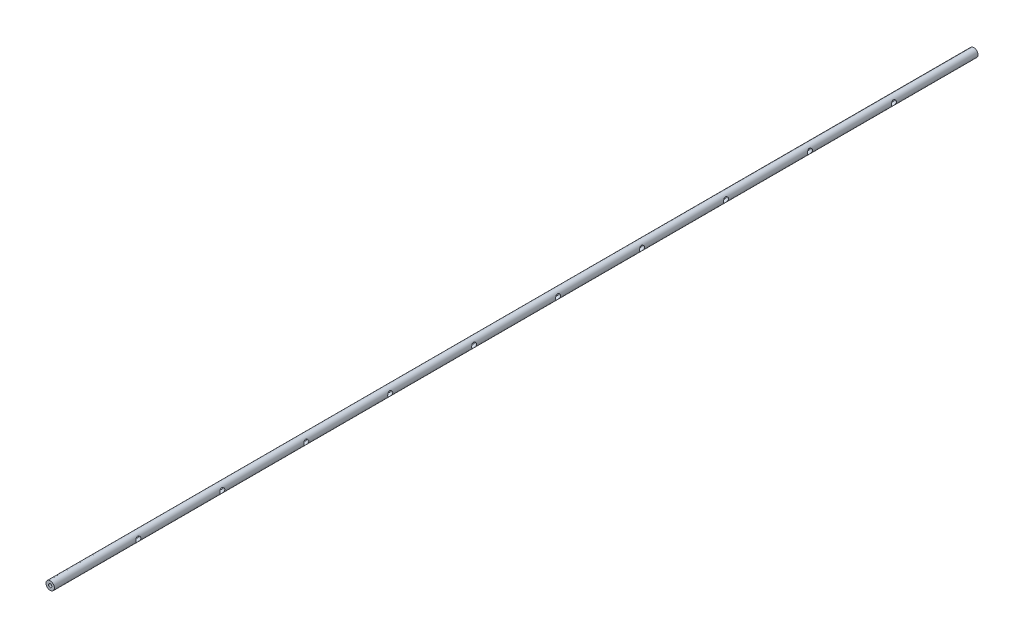
SolidWorks part; units mm, degrees
ref_plane "前视基准面" through (0, 0, 0) normal (0, 0, 1) x (1, 0, 0)
ref_plane "上视基准面" through (0, 0, 0) normal (0, 1, 0) x (1, 0, 0)
ref_plane "右视基准面" through (0, 0, 0) normal (1, 0, 0) x (0, 0, -1)
sketch "草图1" plane through (0, 0, 0) normal (0, 0, 1) x (1, 0, 0)
  circle A0 centre (0, 0) radius 5
  point P2 (0, 0)
extrude "凸台-拉伸1" add sketch "草图1" along normal blind 1100
sketch "草图2" plane through (0, 0, 0) normal (1, 0, 0) x (0, 0, -1)
  circle A0 centre (-100, 0) radius 3
  circle A1 centre (-200, 0) radius 3
  circle A2 centre (-300, 0) radius 3
  circle A3 centre (-400, 0) radius 3
  circle A4 centre (-500, 0) radius 3
  circle A5 centre (-600, 0) radius 3
  circle A6 centre (-700, 0) radius 3
  circle A7 centre (-800, 0) radius 3
  circle A8 centre (-900, 0) radius 3
  circle A9 centre (-1000, 0) radius 3
extrude "切除-拉伸2" cut sketch "草图2" against normal through all both and the other way through all
sketch "草图3" plane through (0, 0, 1100) normal (0, 0, 1) x (1, 0, 0)
  circle A0 centre (0, 0) radius 2
extrude "切除-拉伸3" cut sketch "草图3" against normal through all both and the other way through all
